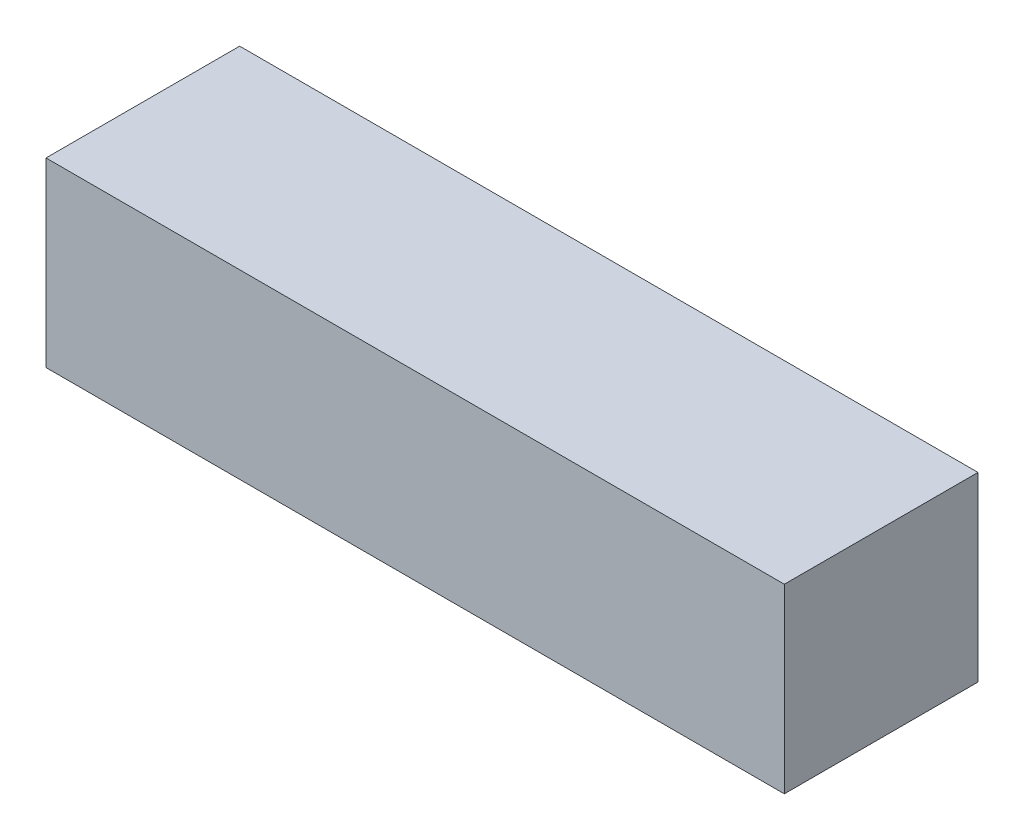
SolidWorks part; units mm, degrees
ref_plane "Front Plane" through (0, 0, 0) normal (0, 0, 1) x (1, 0, 0)
ref_plane "Top Plane" through (0, 0, 0) normal (0, 1, 0) x (1, 0, 0)
ref_plane "Right Plane" through (0, 0, 0) normal (1, 0, 0) x (0, 0, -1)
sketch "Sketch1" plane through (0, 0, 0) normal (0, 1, 0) x (1, 0, 0)
  line L1 (-30.5, -8) -> (30.5, -8)
  line L2 (-30.5, -8) -> (-30.5, 8)
  line L3 (-30.5, 8) -> (30.5, 8)
  line L4 (30.5, -8) -> (30.5, 8)
  line L5 (-30.5, -8) -> (30.5, 8) construction
  line L6 (-30.5, 8) -> (30.5, -8) construction
  point P0 (0, 0)
  dimension "D1" = 16
  dimension "D2" = 61
extrude "Boss-Extrude1" add sketch "Sketch1" along normal mid plane 15
